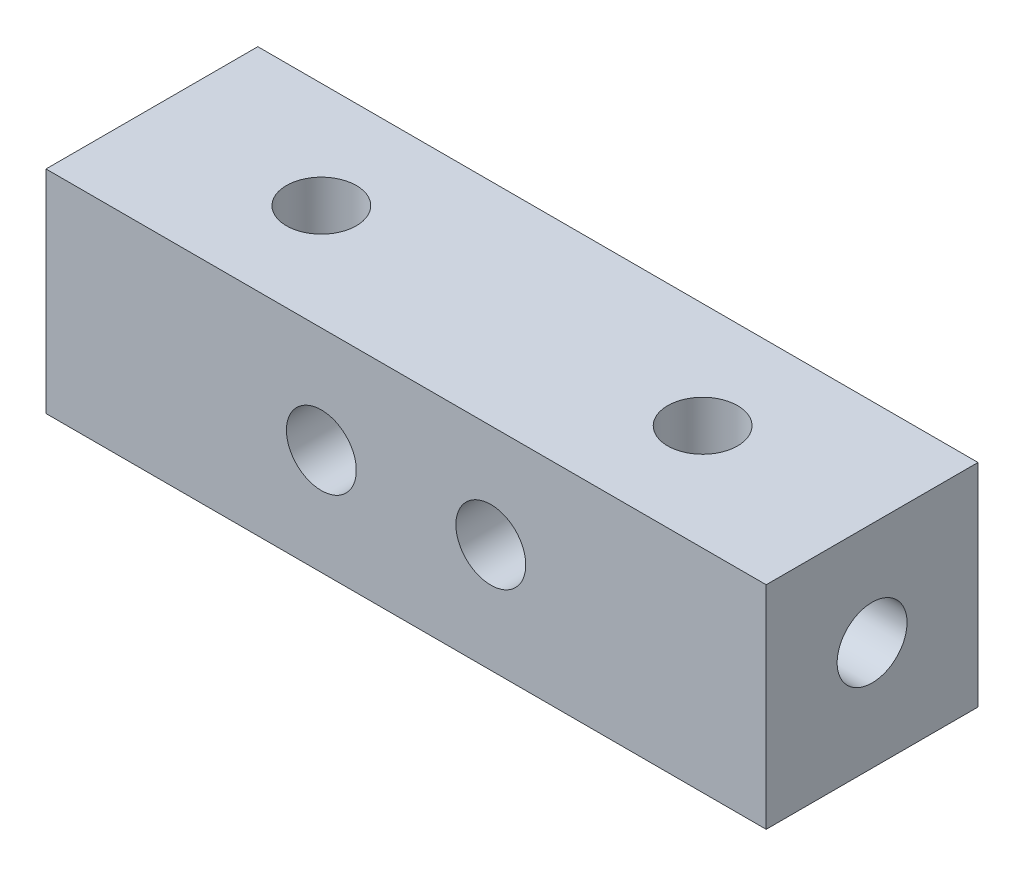
SolidWorks part; units mm, degrees
material "6061 合金"
ref_plane "前视基准面" through (0, 0, 0) normal (0, 0, 1) x (1, 0, 0)
ref_plane "上视基准面" through (0, 0, 0) normal (0, 1, 0) x (1, 0, 0)
ref_plane "右视基准面" through (0, 0, 0) normal (1, 0, 0) x (0, 0, -1)
sketch "草图2" plane through (0, 0, 0) normal (0, 0, 1) x (1, 0, 0)
sketch "草图3" plane through (0, 0, 0) normal (0, 0, 1) x (1, 0, 0)
  line L1 (17, -5) -> (-17, -5)
  line L2 (17, -5) -> (17, 5)
  line L3 (17, 5) -> (-17, 5)
  line L4 (-17, -5) -> (-17, 5)
  line L5 (17, -5) -> (-17, 5) construction
  line L6 (17, 5) -> (-17, -5) construction
  point P0 (0, 0)
  dimension "D1" = 34
  dimension "D2" = 10
extrude "凸台-拉伸2" add sketch "草图3" along normal blind 10
sketch "草图4" plane through (17, 0, 0) normal (1, 0, 0) x (0, 0, -1)
  line L0 (0, 5.2686) -> (-10, -5) construction
  line L1 (0, -5) -> (-10, 5) construction
  point P7 (-5, 0.1343)
hole_wizard "M4 螺纹孔的螺纹孔钻头1" positions "3D草图1" profile "草图5" hole size "M4" standard "DIN" end condition through all
sketch3d "3D草图1"
  point P0 (17, 0.1343, 5)
sketch "草图5" plane through (17, 0.1343, 5) normal (0, 1, 0) x (0, 0, -1)
  line L0 (0, 0) -> (0, 34)
  line L1 (0, 34) -> (1.65, 34)
  line L2 (1.65, 34) -> (1.65, 0)
  line L5 (1.65, 0) -> (0, 0)
  line L11 (0, -6.35) -> (0, 107.95) construction
  dimension "通孔孔直径" = 3.3
  dimension "通孔孔深度" = 34
sketch "草图6" plane through (0, -5, 0) normal (0, -1, 0) x (1, 0, 0)
  line L0 (17, 10) -> (17, 0) construction
  line L1 (-17, 10) -> (-17, 0) construction
  point P0 (9, 5)
  point P1 (-9, 5)
  dimension "D1" = 8
  dimension "D2" = 8
sketch "草图7" plane through (0, 0, 0) normal (0, 0, -1) x (-1, 0, 0)
  line L0 (-17, 5.2686) -> (-17, -5) construction
  line L1 (17, 5) -> (17, -5) construction
  point P0 (-4, 0.1343)
  point P1 (4, 0)
  dimension "D1" = 13
  dimension "D2" = 13
hole_wizard "M4 螺纹孔的螺纹孔钻头2" positions "3D草图2" profile "草图8" hole size "M4" standard "DIN" end condition through all
sketch3d "3D草图2"
  point P0 (9, -5, 5)
sketch "草图8" plane through (9, -5, 5) normal (1, 0, 0) x (0, 0, -1)
  line L0 (0, 0) -> (0, 10)
  line L1 (0, 10) -> (1.65, 10)
  line L2 (1.65, 10) -> (1.65, 0)
  line L5 (1.65, 0) -> (0, 0)
  line L11 (0, -6.35) -> (0, 107.95) construction
  dimension "通孔孔直径" = 3.3
  dimension "通孔孔深度" = 10
hole_wizard "M4 螺纹孔的螺纹孔钻头3" positions "3D草图3" profile "草图9" hole size "M4" standard "DIN" end condition through all
sketch3d "3D草图3"
  point P0 (-9, -5, 5)
sketch "草图9" plane through (-9, -5, 5) normal (1, 0, 0) x (0, 0, -1)
  line L0 (0, 0) -> (0, 10)
  line L1 (0, 10) -> (1.65, 10)
  line L2 (1.65, 10) -> (1.65, 0)
  line L5 (1.65, 0) -> (0, 0)
  line L11 (0, -6.35) -> (0, 107.95) construction
  dimension "通孔孔直径" = 3.3
  dimension "通孔孔深度" = 10
hole_wizard "M4 螺纹孔的螺纹孔钻头4" positions "3D草图4" profile "草图10" hole size "M4" standard "DIN" end condition through all
sketch3d "3D草图4"
  point P0 (4, 0.1343, 0)
sketch "草图10" plane through (4, 0.1343, 0) normal (1, 0, 0) x (0, 1, 0)
  line L0 (0, 0) -> (0, 10)
  line L1 (0, 10) -> (1.65, 10)
  line L2 (1.65, 10) -> (1.65, 0)
  line L5 (1.65, 0) -> (0, 0)
  line L11 (0, -6.35) -> (0, 107.95) construction
  dimension "通孔孔直径" = 3.3
  dimension "通孔孔深度" = 10
hole_wizard "M4 螺纹孔的螺纹孔钻头5" positions "3D草图5" profile "草图11" hole size "M4" standard "DIN" end condition through all
sketch3d "3D草图5"
  point P0 (-4, 0, 0)
sketch "草图11" plane through (-4, 0, 0) normal (1, 0, 0) x (0, 1, 0)
  line L0 (0, 0) -> (0, 10)
  line L1 (0, 10) -> (1.65, 10)
  line L2 (1.65, 10) -> (1.65, 0)
  line L5 (1.65, 0) -> (0, 0)
  line L11 (0, -6.35) -> (0, 107.95) construction
  dimension "通孔孔直径" = 3.3
  dimension "通孔孔深度" = 10
